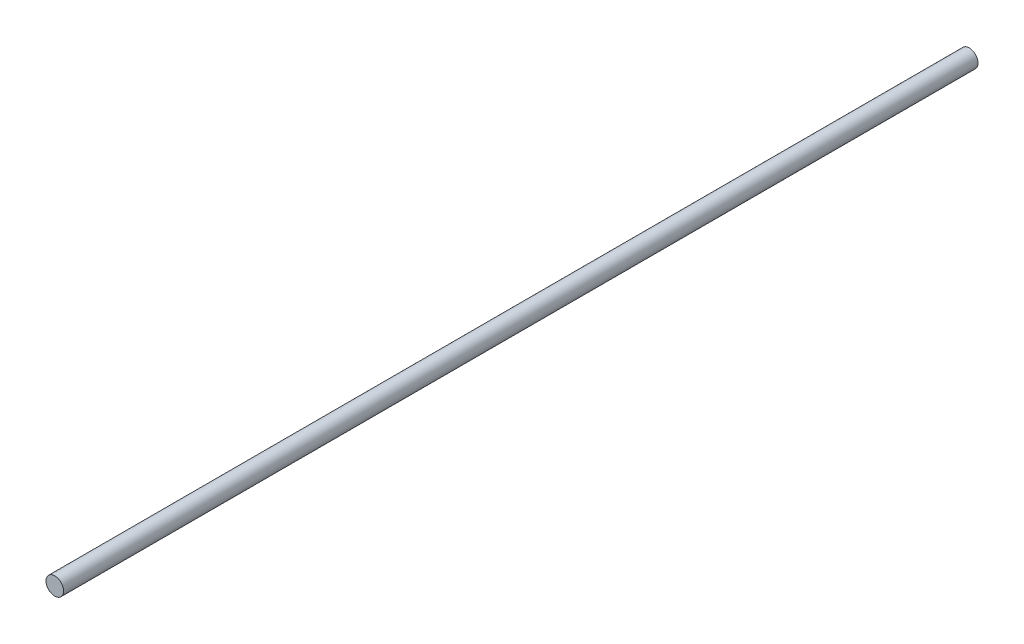
SolidWorks part; units mm, degrees
ref_plane "Front Plane" through (0, 0, 0) normal (0, 0, 1) x (1, 0, 0)
ref_plane "Top Plane" through (0, 0, 0) normal (0, 1, 0) x (1, 0, 0)
ref_plane "Right Plane" through (0, 0, 0) normal (1, 0, 0) x (0, 0, -1)
sketch "Sketch1" plane through (0, 0, 0) normal (0, 0, 1) x (1, 0, 0)
  circle A0 centre (0, 0) radius 1
extrude "Boss-Extrude1" add sketch "Sketch1" along normal blind 104
